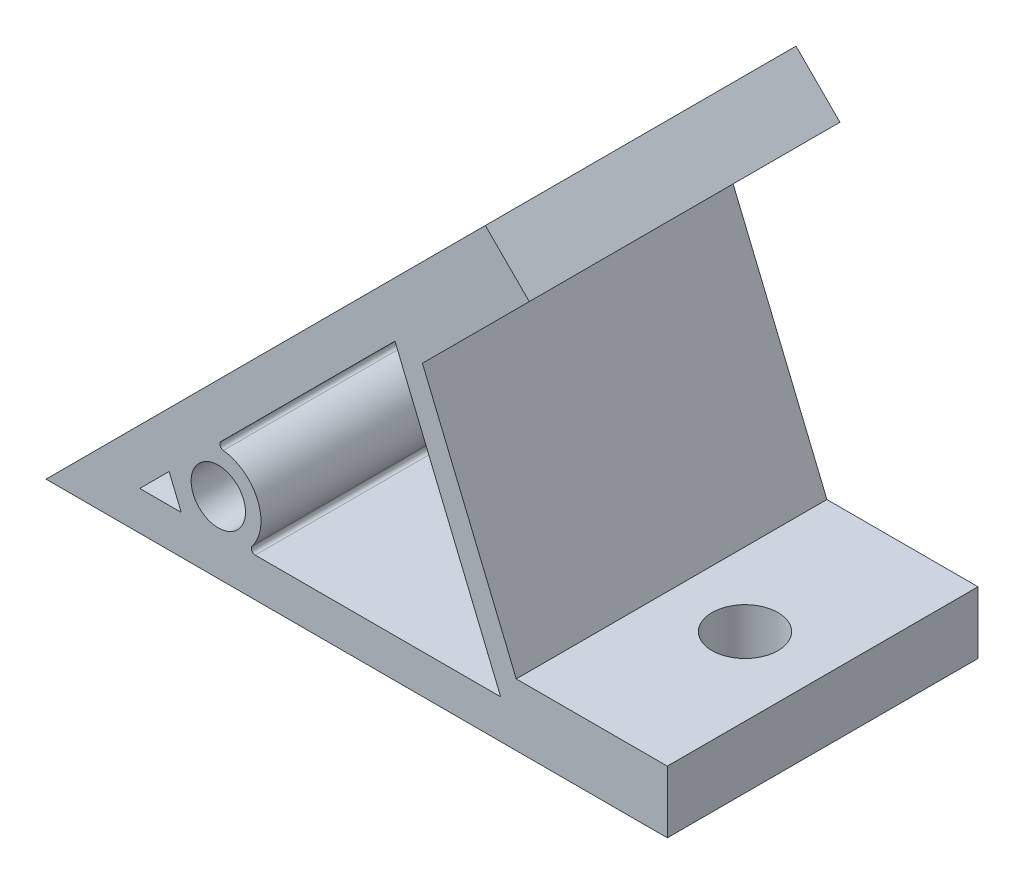
SolidWorks part; units mm, degrees
ref_plane "前视基准面" through (0, 0, 0) normal (0, 0, 1) x (1, 0, 0)
ref_plane "上视基准面" through (0, 0, 0) normal (0, 1, 0) x (1, 0, 0)
ref_plane "右视基准面" through (0, 0, 0) normal (1, 0, 0) x (0, 0, -1)
sketch "草图1" plane through (0, 0, 0) normal (0, 0, 1) x (1, 0, 0)
  line L0 (0, 0) -> (56.5685, 56.5685)
  line L1 (0, 0) -> (80, 0)
  line L2 (12.0711, 5) -> (15.8477, 8.7766)
  line L3 (12.0711, 5) -> (17.412, 5)
  line L4 (15.8477, 8.7766) -> (17.412, 5)
  line L5 (0, 0) -> (16.6385, 6.8674) construction
  line L6 (22.5392, 15.4681) -> (44.9316, 37.8605)
  line L7 (26.9418, 5) -> (58.5429, 5)
  line L8 (12.0711, 5) -> (60.1041, 53.033) construction
  line L9 (58.5429, 5) -> (44.9316, 37.8605)
  line L10 (12.0711, 5) -> (80, 5) construction
  line L11 (60.5474, 8) -> (48.4704, 37.1566)
  line L12 (61.3145, 6.1481) -> (47.7033, 39.0086) construction
  line L13 (62.2254, 50.9117) -> (56.5685, 56.5685)
  line L14 (80, 0) -> (80, 8)
  line L15 (60.5474, 8) -> (80, 8)
  line L16 (50.7665, 39.4527) -> (62.2254, 50.9117) construction
  line L17 (48.4704, 37.1566) -> (62.2254, 50.9117)
  line L18 (63.7946, 8) -> (50.7665, 39.4527) construction
  line L19 (63.7946, 8) -> (80, 8) construction
  line L20 (61.7901, 5) -> (80, 5) construction
  line L21 (47.2277, 40.1566) -> (60.1041, 53.033) construction
  line L23 (61.7901, 5) -> (47.2277, 40.1566) construction
  circle A0 centre (22.1847, 9.1565) radius 3.5
  arc A1 (26.5454, 5.8047) -> (22.8337, 14.618) centre (22.1847, 9.1565) ccw
  arc A2 (26.9418, 5) -> (26.5454, 5.8047) centre (26.9418, 5.5) cw
  circle A3 centre (22.1847, 9.1565) radius 5.5 construction
  arc A4 (22.5392, 15.4681) -> (22.8337, 14.618) centre (22.8927, 15.1145) ccw
  point P15 (27.6847, 9.1565)
  point P20 (25.7866, 5)
  point P23 (21.7067, 14.6357)
  dimension "D7" = 7
  dimension "D8" = 2
  dimension "D9" = 0.5
  dimension "D10" = 56
  dimension "D1" = 45
  dimension "D2" = 80
  dimension "D4" = 67.5
  dimension "D5" = 18
  dimension "D6" = 6
  dimension "D3" = 5
  dimension "D11" = 3
  dimension "D12" = 3
extrude "凸台-拉伸1" add sketch "草图1" along normal mid plane 40
sketch "草图2" plane through (0, 0, 0) normal (-0.7071, 0.7071, 0) x (0, 0, 1)
  line L0 (0, 80) -> (0, 53.9096) construction
  line L1 (20, 80) -> (-20, 80) construction
  circle A0 centre (0, 70) radius 4.25
  dimension "D1" = 10
  dimension "D3" = 8.5
extrude "切除-拉伸1" cut sketch "草图2" against normal blind 20
sketch "草图3" plane through (0, 0, 0) normal (0, -1, 0) x (1, 0, 0)
  line L0 (80, 0) -> (48.7562, 0) construction
  line L1 (80, 20) -> (80, -20) construction
  circle A0 centre (70, 0) radius 4.25
  dimension "D2" = 10
  dimension "D3" = 8.5
extrude "切除-拉伸2" cut sketch "草图3" against normal blind 20
